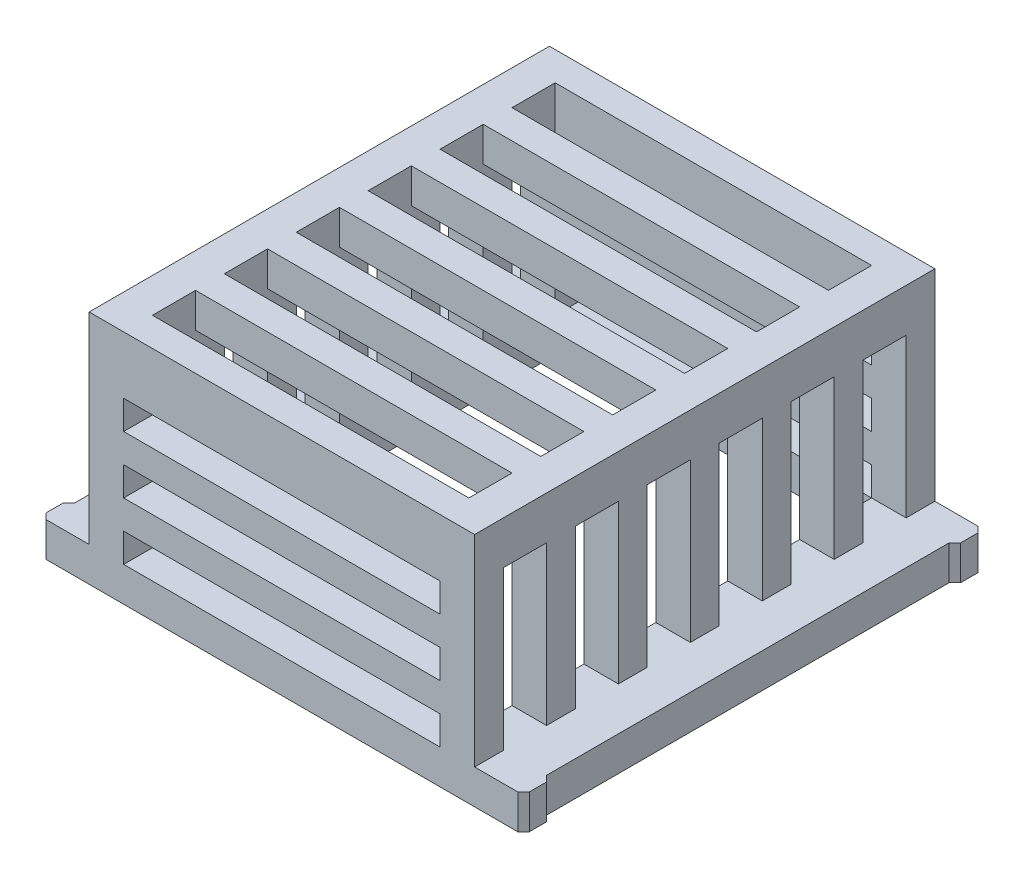
SolidWorks part; units mm, degrees
ref_plane "Front Plane" through (0, 0, 0) normal (0, 0, 1) x (1, 0, 0)
ref_plane "Top Plane" through (0, 0, 0) normal (0, 1, 0) x (1, 0, 0)
ref_plane "Right Plane" through (0, 0, 0) normal (1, 0, 0) x (0, 0, -1)
sketch "Sketch1" plane through (0, 0, 0) normal (0, 0, 1) x (1, 0, 0)
  line L0 (-13.608, -5.7035) -> (-13.608, -8.1035)
  line L1 (-13.608, -8.1035) -> (-8.208, -8.1035)
  line L2 (2.792, -6.1402) -> (2.792, 21.2678) construction
  line L3 (-13.608, -5.7035) -> (-10.608, -5.7035)
  line L4 (-10.608, -5.7035) -> (-10.608, 8.2965)
  line L5 (-10.608, 8.2965) -> (16.192, 8.2965)
  line L6 (-8.208, -8.1035) -> (-8.208, 5.8965)
  line L7 (-8.208, 5.8965) -> (13.792, 5.8965)
  line L8 (13.792, -8.1035) -> (13.792, 5.8965)
  line L9 (16.192, -5.7035) -> (16.192, 8.2965)
  line L10 (19.192, -5.7035) -> (16.192, -5.7035)
  line L11 (19.192, -8.1035) -> (13.792, -8.1035)
  line L12 (19.192, -5.7035) -> (19.192, -8.1035)
  point P2 (-10.908, -8.1035)
  point P12 (2.792, 5.8965)
  point P13 (2.792, 8.2965)
  point P17 (0, 0)
  dimension "D1" = 2.4
  dimension "D2" = 3
  dimension "D3" = 2.4
  dimension "D4" = 2.4
  dimension "D5" = 14
  dimension "D6" = 16.4
extrude "Boss-Extrude1" add sketch "Sketch1" along normal blind 32
sketch "Sketch2" plane through (0, 5.8965, 0) normal (0, -1, 0) x (1, 0, 0)
  line L0 (13.792, 32) -> (13.792, 0) construction
  line L1 (-8.208, 32) -> (13.792, 32)
  line L2 (-8.208, 32) -> (-8.208, 30)
  line L3 (-8.208, 30) -> (13.792, 30)
  line L4 (13.792, 32) -> (13.792, 30)
  line L6 (-8.208, 0) -> (13.792, 0)
  line L7 (-8.208, 0) -> (-8.208, 2)
  line L8 (-8.208, 2) -> (13.792, 2)
  line L9 (13.792, 0) -> (13.792, 2)
  dimension "D1" = 2
  dimension "D2" = 2
extrude "Boss-Extrude2" add sketch "Sketch2" along normal up to surface (14 mm away) up to face at (-10.908, -8.1035, 16)
sketch "Sketch4" plane through (-10.608, 0, 0) normal (-1, 0, 0) x (0, 0, 1)
  line L0 (32, 8.2965) -> (32, -5.7035) construction
  line L1 (30, -5.7035) -> (27, -5.7035)
  line L2 (30, -5.7035) -> (30, 5.2965)
  line L3 (30, 5.2965) -> (27, 5.2965)
  line L4 (27, -5.7035) -> (27, 5.2965)
  line L5 (32, -5.7035) -> (0, -5.7035) construction
  line L7 (32, 8.2965) -> (0, 8.2965) construction
  dimension "D1" = 2
  dimension "D2" = 3
  dimension "D3" = 3
extrude "Cut-Extrude2" cut sketch "Sketch4" against normal through all
pattern_linear "LPattern1" count 6 spacing 5 along (0, 0, -1) of "Cut-Extrude2"
sketch "Sketch5" plane through (0, 5.8965, 0) normal (0, -1, 0) x (1, 0, 0)
  line L0 (-8.208, 30) -> (-8.208, 2) construction
  line L1 (13.792, 30) -> (-8.208, 30)
  line L2 (13.792, 30) -> (13.792, 27)
  line L3 (13.792, 27) -> (-8.208, 27)
  line L4 (-8.208, 30) -> (-8.208, 27)
  dimension "D1" = 3
extrude "Cut-Extrude3" cut sketch "Sketch5" against normal through all
pattern_linear "LPattern2" count 6 spacing 5 along (0, 0, -1) of "Cut-Extrude3"
sketch "Sketch6" plane through (0, 0, 30) normal (0, 0, -1) x (-1, 0, 0)
  line L1 (8.208, -5.7035) -> (-13.792, -5.7035)
  line L2 (8.208, -5.7035) -> (8.208, -3.7035)
  line L3 (8.208, -3.7035) -> (-13.792, -3.7035)
  line L4 (-13.792, -5.7035) -> (-13.792, -3.7035)
  point P5 (0, 0)
  dimension "D1" = 2
extrude "Cut-Extrude4" cut sketch "Sketch6" against normal through all and the other way through all
pattern_linear "LPattern3" count 3 spacing 4 along (0, 1, 0) of "Cut-Extrude4"
sketch "Sketch8" plane through (0, -8.1035, 0) normal (0, -1, 0) x (1, 0, 0)
  line L0 (-13.608, 30) -> (-14.008, 30.4)
  line L1 (-13.608, 32) -> (-13.608, 0) construction
  line L2 (-14.008, 30.4) -> (-14.008, 31.6)
  line L3 (-14.008, 31.6) -> (-13.608, 32)
  line L4 (-13.608, 30) -> (-13.608, 32)
  line L5 (-13.608, 32) -> (19.192, 32) construction
  line L6 (2.792, 32) -> (2.792, 0) construction
  line L7 (-13.608, 0) -> (19.192, 0) construction
  line L8 (-13.608, 16) -> (19.192, 16) construction
  line L9 (19.192, 32) -> (19.192, 0) construction
  line L10 (-13.608, 2) -> (-13.608, 0)
  line L11 (-14.008, 0.4) -> (-13.608, 0)
  line L12 (-14.008, 1.6) -> (-14.008, 0.4)
  line L13 (-13.608, 2) -> (-14.008, 1.6)
  line L14 (19.192, 2) -> (19.592, 1.6)
  line L15 (19.592, 1.6) -> (19.592, 0.4)
  line L16 (19.592, 0.4) -> (19.192, 0)
  line L17 (19.192, 2) -> (19.192, 0)
  line L18 (19.192, 30) -> (19.192, 32)
  line L19 (19.592, 31.6) -> (19.192, 32)
  line L20 (19.592, 30.4) -> (19.592, 31.6)
  line L21 (19.192, 30) -> (19.592, 30.4)
  point P9 (-13.608, 31)
  point P10 (-14.008, 31)
  point P31 (-14.008, 30.4)
  dimension "D1" = 0.4
  dimension "D2" = 2
extrude "Boss-Extrude3" add sketch "Sketch8" against normal up to surface (2.4 mm away) up to face at (-9.7937, -5.7035, 16)
